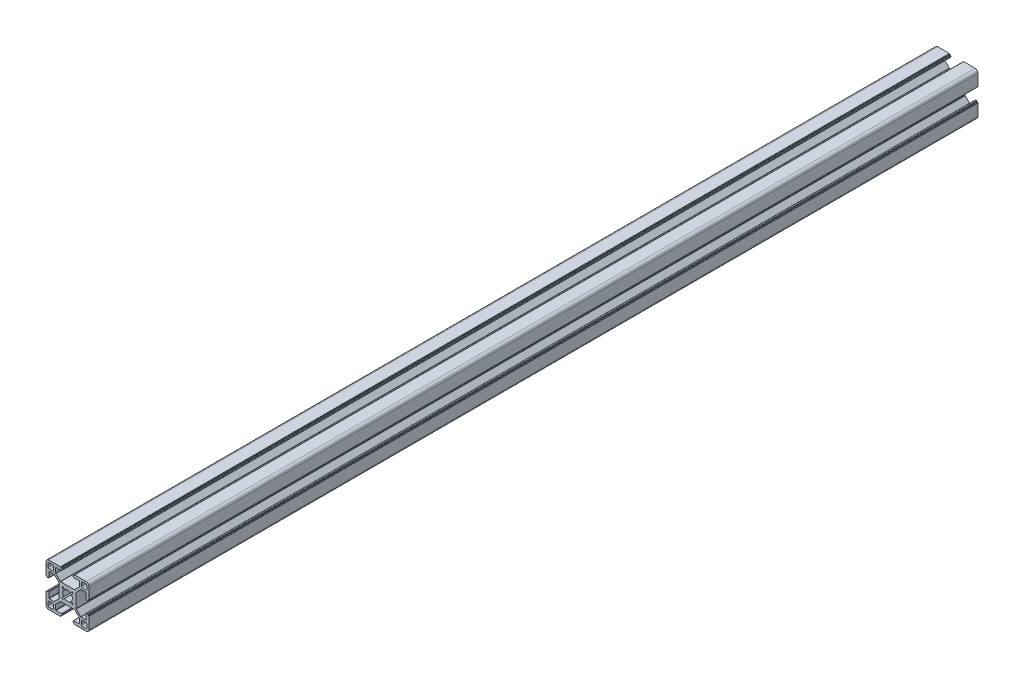
SolidWorks part; units mm, degrees
ref_plane "Piano frontale" through (0, 0, 0) normal (0, 0, 1) x (1, 0, 0)
ref_plane "Piano superiore" through (0, 0, 0) normal (0, 1, 0) x (1, 0, 0)
ref_plane "Piano destro" through (0, 0, 0) normal (1, 0, 0) x (0, 0, -1)
ref_plane "Piano1" through (0, 0, 25) normal (0, 0, 1) x (1, 0, 0)
sketch "Schizzo1" plane through (0, 0, 25) normal (0, 0, 1) x (1, 0, 0)
  line L0 (-12.5625, -9.75) -> (-10.6875, -9.75)
  line L1 (-9.75, -10.6875) -> (-9.75, -12.5625)
  line L2 (-10.6875, -13.5) -> (-12.5625, -13.5)
  line L3 (-13.5, -12.5625) -> (-13.5, -10.6875)
  line L4 (12.5625, 9.75) -> (10.6875, 9.75)
  line L5 (9.75, 10.6875) -> (9.75, 12.5625)
  line L6 (10.6875, 13.5) -> (12.5625, 13.5)
  line L7 (13.5, 12.5625) -> (13.5, 10.6875)
  line L8 (-4.7, -14.7) -> (-4.7, -14.6)
  line L9 (-4.4, -14.3) -> (-4.3, -14.3)
  line L10 (-4, -14) -> (-4, -13.3)
  line L11 (-4.3, -13) -> (-7.95, -13)
  line L12 (-8.25, -12.7) -> (-8.25, -9.4349)
  line L13 (-8.1621, -9.2228) -> (-5.0272, -6.0879)
  line L14 (-4.8151, -6) -> (4.8151, -6)
  line L15 (5.0272, -6.0879) -> (8.1621, -9.2228)
  line L16 (8.25, -9.4349) -> (8.25, -12.7)
  line L17 (7.95, -13) -> (4.3, -13)
  line L18 (4, -13.3) -> (4, -14)
  line L19 (4.3, -14.3) -> (4.4, -14.3)
  line L20 (4.7, -14.6) -> (4.7, -14.7)
  line L21 (5, -15) -> (13, -15)
  line L22 (15, -13) -> (15, -5)
  line L23 (14.7, -4.7) -> (14.6, -4.7)
  line L24 (14.3, -4.4) -> (14.3, -4.3)
  line L25 (14, -4) -> (13.3, -4)
  line L26 (13, -4.3) -> (13, -7.95)
  line L27 (12.7, -8.25) -> (9.4349, -8.25)
  line L28 (9.2228, -8.1621) -> (6.0879, -5.0272)
  line L29 (6, -4.8151) -> (6, 4.8151)
  line L30 (6.0879, 5.0272) -> (9.2228, 8.1621)
  line L31 (9.4349, 8.25) -> (12.7, 8.25)
  line L32 (13, 7.95) -> (13, 4.3)
  line L33 (13.3, 4) -> (14, 4)
  line L34 (14.3, 4.3) -> (14.3, 4.4)
  line L35 (14.6, 4.7) -> (14.7, 4.7)
  line L36 (15, 5) -> (15, 13)
  line L37 (13, 15) -> (5, 15)
  line L38 (4.7, 14.7) -> (4.7, 14.6)
  line L39 (4.4, 14.3) -> (4.3, 14.3)
  line L40 (4, 14) -> (4, 13.3)
  line L41 (4.3, 13) -> (7.95, 13)
  line L42 (8.25, 12.7) -> (8.25, 9.4349)
  line L43 (8.1621, 9.2228) -> (5.0272, 6.0879)
  line L44 (4.8151, 6) -> (-4.8151, 6)
  line L45 (-5.0272, 6.0879) -> (-8.1621, 9.2228)
  line L46 (-8.25, 9.4349) -> (-8.25, 12.7)
  line L47 (-7.95, 13) -> (-4.3, 13)
  line L48 (-4, 13.3) -> (-4, 14)
  line L49 (-4.3, 14.3) -> (-4.4, 14.3)
  line L50 (-4.7, 14.6) -> (-4.7, 14.7)
  line L51 (-5, 15) -> (-13, 15)
  line L52 (-15, 13) -> (-15, 5)
  line L53 (-14.7, 4.7) -> (-14.6, 4.7)
  line L54 (-14.3, 4.4) -> (-14.3, 4.3)
  line L55 (-14, 4) -> (-13.3, 4)
  line L56 (-13, 4.3) -> (-13, 7.95)
  line L57 (-12.7, 8.25) -> (-9.4349, 8.25)
  line L58 (-9.2228, 8.1621) -> (-6.0879, 5.0272)
  line L59 (-6, 4.8151) -> (-6, -4.8151)
  line L60 (-6.0879, -5.0272) -> (-9.2228, -8.1621)
  line L61 (-9.4349, -8.25) -> (-12.7, -8.25)
  line L62 (-13, -7.95) -> (-13, -4.3)
  line L63 (-13.3, -4) -> (-14, -4)
  line L64 (-14.3, -4.3) -> (-14.3, -4.4)
  line L65 (-14.6, -4.7) -> (-14.7, -4.7)
  line L66 (-15, -5) -> (-15, -13)
  line L67 (-13, -15) -> (-5, -15)
  line L68 (2.0101, 2.7422) -> (2.8679, 3.6)
  line L69 (3.6, 2.8679) -> (2.7422, 2.0101)
  line L70 (2.7422, -2.0101) -> (3.6, -2.8679)
  line L71 (2.8679, -3.6) -> (2.0101, -2.7422)
  line L72 (-2.0101, -2.7422) -> (-2.8679, -3.6)
  line L73 (-3.6, -2.8679) -> (-2.7422, -2.0101)
  line L74 (-2.7422, 2.0101) -> (-3.6, 2.8679)
  line L75 (-2.8679, 3.6) -> (-2.0101, 2.7422)
  line L76 (-9.75, 12.5625) -> (-9.75, 10.6875)
  line L77 (-10.6875, 9.75) -> (-12.5625, 9.75)
  line L78 (-13.5, 10.6875) -> (-13.5, 12.5625)
  line L79 (-12.5625, 13.5) -> (-10.6875, 13.5)
  line L80 (9.75, -12.5625) -> (9.75, -10.6875)
  line L81 (10.6875, -9.75) -> (12.5625, -9.75)
  line L82 (13.5, -10.6875) -> (13.5, -12.5625)
  line L83 (12.5625, -13.5) -> (10.6875, -13.5)
  arc A0 (-10.6875, -9.75) -> (-9.75, -10.6875) centre (-10.6875, -10.6875) cw
  arc A1 (-9.75, -12.5625) -> (-10.6875, -13.5) centre (-10.6875, -12.5625) cw
  arc A2 (-12.5625, -13.5) -> (-13.5, -12.5625) centre (-12.5625, -12.5625) cw
  arc A3 (-13.5, -10.6875) -> (-12.5625, -9.75) centre (-12.5625, -10.6875) cw
  arc A4 (10.6875, 9.75) -> (9.75, 10.6875) centre (10.6875, 10.6875) cw
  arc A5 (9.75, 12.5625) -> (10.6875, 13.5) centre (10.6875, 12.5625) cw
  arc A6 (12.5625, 13.5) -> (13.5, 12.5625) centre (12.5625, 12.5625) cw
  arc A7 (13.5, 10.6875) -> (12.5625, 9.75) centre (12.5625, 10.6875) cw
  arc A8 (-5, -15) -> (-4.7, -14.7) centre (-5, -14.7) ccw
  arc A9 (-4.7, -14.6) -> (-4.4, -14.3) centre (-4.4, -14.6) cw
  arc A10 (-4.3, -14.3) -> (-4, -14) centre (-4.3, -14) ccw
  arc A11 (-4, -13.3) -> (-4.3, -13) centre (-4.3, -13.3) ccw
  arc A12 (-7.95, -13) -> (-8.25, -12.7) centre (-7.95, -12.7) cw
  arc A13 (-8.25, -9.4349) -> (-8.1621, -9.2228) centre (-7.95, -9.4349) cw
  arc A14 (-5.0272, -6.0879) -> (-4.8151, -6) centre (-4.8151, -6.3) cw
  arc A15 (4.8151, -6) -> (5.0272, -6.0879) centre (4.8151, -6.3) cw
  arc A16 (8.1621, -9.2228) -> (8.25, -9.4349) centre (7.95, -9.4349) cw
  arc A17 (8.25, -12.7) -> (7.95, -13) centre (7.95, -12.7) cw
  arc A18 (4.3, -13) -> (4, -13.3) centre (4.3, -13.3) ccw
  arc A19 (4, -14) -> (4.3, -14.3) centre (4.3, -14) ccw
  arc A20 (4.4, -14.3) -> (4.7, -14.6) centre (4.4, -14.6) cw
  arc A21 (4.7, -14.7) -> (5, -15) centre (5, -14.7) ccw
  arc A22 (13, -15) -> (15, -13) centre (13, -13) ccw
  arc A23 (15, -5) -> (14.7, -4.7) centre (14.7, -5) ccw
  arc A24 (14.6, -4.7) -> (14.3, -4.4) centre (14.6, -4.4) cw
  arc A25 (14.3, -4.3) -> (14, -4) centre (14, -4.3) ccw
  arc A26 (13.3, -4) -> (13, -4.3) centre (13.3, -4.3) ccw
  arc A27 (13, -7.95) -> (12.7, -8.25) centre (12.7, -7.95) cw
  arc A28 (9.4349, -8.25) -> (9.2228, -8.1621) centre (9.4349, -7.95) cw
  arc A29 (6.0879, -5.0272) -> (6, -4.8151) centre (6.3, -4.8151) cw
  arc A30 (6, 4.8151) -> (6.0879, 5.0272) centre (6.3, 4.8151) cw
  arc A31 (9.2228, 8.1621) -> (9.4349, 8.25) centre (9.4349, 7.95) cw
  arc A32 (12.7, 8.25) -> (13, 7.95) centre (12.7, 7.95) cw
  arc A33 (13, 4.3) -> (13.3, 4) centre (13.3, 4.3) ccw
  arc A34 (14, 4) -> (14.3, 4.3) centre (14, 4.3) ccw
  arc A35 (14.3, 4.4) -> (14.6, 4.7) centre (14.6, 4.4) cw
  arc A36 (14.7, 4.7) -> (15, 5) centre (14.7, 5) ccw
  arc A37 (15, 13) -> (13, 15) centre (13, 13) ccw
  arc A38 (5, 15) -> (4.7, 14.7) centre (5, 14.7) ccw
  arc A39 (4.7, 14.6) -> (4.4, 14.3) centre (4.4, 14.6) cw
  arc A40 (4.3, 14.3) -> (4, 14) centre (4.3, 14) ccw
  arc A41 (4, 13.3) -> (4.3, 13) centre (4.3, 13.3) ccw
  arc A42 (7.95, 13) -> (8.25, 12.7) centre (7.95, 12.7) cw
  arc A43 (8.25, 9.4349) -> (8.1621, 9.2228) centre (7.95, 9.4349) cw
  arc A44 (5.0272, 6.0879) -> (4.8151, 6) centre (4.8151, 6.3) cw
  arc A45 (-4.8151, 6) -> (-5.0272, 6.0879) centre (-4.8151, 6.3) cw
  arc A46 (-8.1621, 9.2228) -> (-8.25, 9.4349) centre (-7.95, 9.4349) cw
  arc A47 (-8.25, 12.7) -> (-7.95, 13) centre (-7.95, 12.7) cw
  arc A48 (-4.3, 13) -> (-4, 13.3) centre (-4.3, 13.3) ccw
  arc A49 (-4, 14) -> (-4.3, 14.3) centre (-4.3, 14) ccw
  arc A50 (-4.4, 14.3) -> (-4.7, 14.6) centre (-4.4, 14.6) cw
  arc A51 (-4.7, 14.7) -> (-5, 15) centre (-5, 14.7) ccw
  arc A52 (-13, 15) -> (-15, 13) centre (-13, 13) ccw
  arc A53 (-15, 5) -> (-14.7, 4.7) centre (-14.7, 5) ccw
  arc A54 (-14.6, 4.7) -> (-14.3, 4.4) centre (-14.6, 4.4) cw
  arc A55 (-14.3, 4.3) -> (-14, 4) centre (-14, 4.3) ccw
  arc A56 (-13.3, 4) -> (-13, 4.3) centre (-13.3, 4.3) ccw
  arc A57 (-13, 7.95) -> (-12.7, 8.25) centre (-12.7, 7.95) cw
  arc A58 (-9.4349, 8.25) -> (-9.2228, 8.1621) centre (-9.4349, 7.95) cw
  arc A59 (-6.0879, 5.0272) -> (-6, 4.8151) centre (-6.3, 4.8151) cw
  arc A60 (-6, -4.8151) -> (-6.0879, -5.0272) centre (-6.3, -4.8151) cw
  arc A61 (-9.2228, -8.1621) -> (-9.4349, -8.25) centre (-9.4349, -7.95) cw
  arc A62 (-12.7, -8.25) -> (-13, -7.95) centre (-12.7, -7.95) cw
  arc A63 (-13, -4.3) -> (-13.3, -4) centre (-13.3, -4.3) ccw
  arc A64 (-14, -4) -> (-14.3, -4.3) centre (-14, -4.3) ccw
  arc A65 (-14.3, -4.4) -> (-14.6, -4.7) centre (-14.6, -4.4) cw
  arc A66 (-14.7, -4.7) -> (-15, -5) centre (-14.7, -5) ccw
  arc A67 (-15, -13) -> (-13, -15) centre (-13, -13) ccw
  arc A68 (2.8679, 3.6) -> (3.6, 2.8679) centre (3.234, 3.234) cw
  arc A69 (2.7422, 2.0101) -> (2.7422, -2.0101) centre (0, 0) cw
  arc A70 (3.6, -2.8679) -> (2.8679, -3.6) centre (3.234, -3.234) cw
  arc A71 (2.0101, -2.7422) -> (-2.0101, -2.7422) centre (0, 0) cw
  arc A72 (-2.8679, -3.6) -> (-3.6, -2.8679) centre (-3.234, -3.234) cw
  arc A73 (-2.7422, -2.0101) -> (-2.7422, 2.0101) centre (0, 0) cw
  arc A74 (-3.6, 2.8679) -> (-2.8679, 3.6) centre (-3.234, 3.234) cw
  arc A75 (-2.0101, 2.7422) -> (2.0101, 2.7422) centre (0, 0) cw
  arc A76 (-9.75, 10.6875) -> (-10.6875, 9.75) centre (-10.6875, 10.6875) cw
  arc A77 (-12.5625, 9.75) -> (-13.5, 10.6875) centre (-12.5625, 10.6875) cw
  arc A78 (-13.5, 12.5625) -> (-12.5625, 13.5) centre (-12.5625, 12.5625) cw
  arc A79 (-10.6875, 13.5) -> (-9.75, 12.5625) centre (-10.6875, 12.5625) cw
  arc A80 (9.75, -10.6875) -> (10.6875, -9.75) centre (10.6875, -10.6875) cw
  arc A81 (12.5625, -9.75) -> (13.5, -10.6875) centre (12.5625, -10.6875) cw
  arc A82 (13.5, -12.5625) -> (12.5625, -13.5) centre (12.5625, -12.5625) cw
  arc A83 (10.6875, -13.5) -> (9.75, -12.5625) centre (10.6875, -12.5625) cw
extrude "Estrusione-Estrusione1" add sketch "Schizzo1" against normal blind 620
